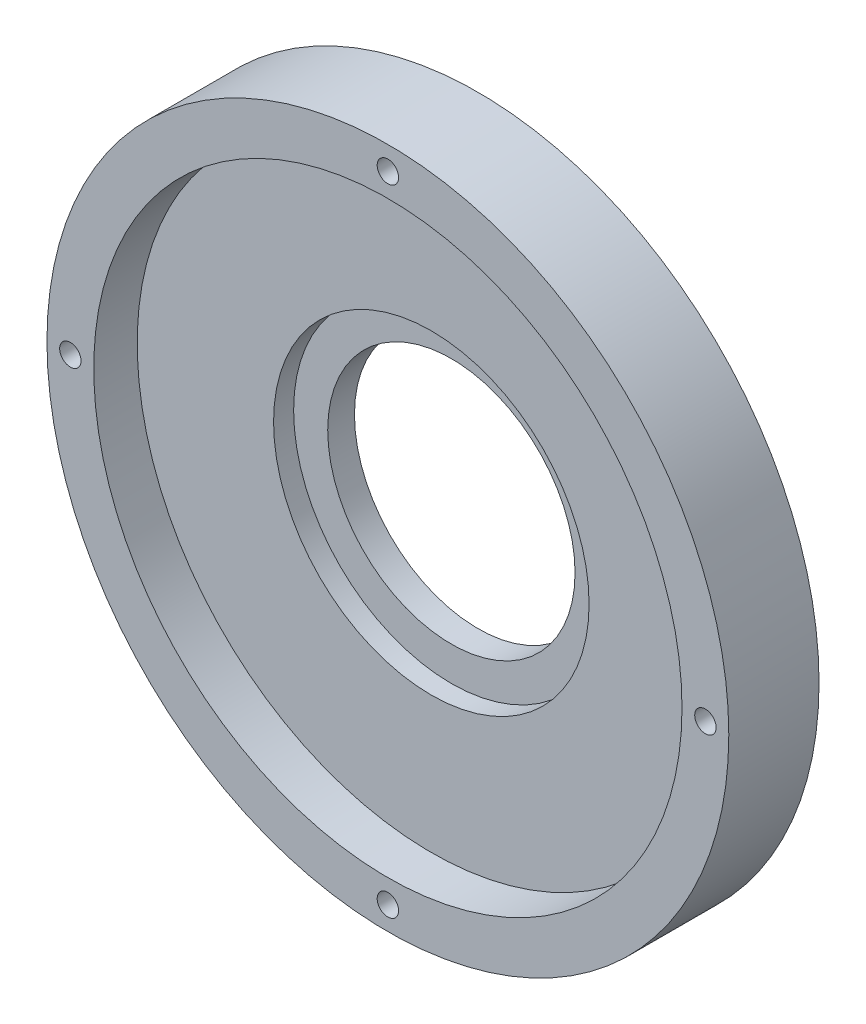
SolidWorks part; units mm, degrees
ref_plane "Front Plane" through (0, 0, 0) normal (0, 0, 1) x (1, 0, 0)
ref_plane "Top Plane" through (0, 0, 0) normal (0, 1, 0) x (1, 0, 0)
ref_plane "Right Plane" through (0, 0, 0) normal (1, 0, 0) x (0, 0, -1)
sketch "Sketch1" plane through (0, 0, 0) normal (0, 0, 1) x (1, 0, 0)
  circle A0 centre (0, 0) radius 51
  dimension "D1" = 102
extrude "Boss-Extrude1" add sketch "Sketch1" along normal blind 13.5
shell "Shell1" thickness 7
sketch "Sketch2" plane through (0, 0, 0) normal (0, 0, -1) x (-1, 0, 0)
  circle A0 centre (0, 0) radius 18.5
  dimension "D1" = 37
extrude "Cut-Extrude1" cut sketch "Sketch2" against normal up to surface (7 mm away) up to face at (44, 0, 7)
sketch "Sketch3" plane through (0, 0, 7) normal (0, 0, 1) x (1, 0, 0)
  circle A0 centre (0, 0) radius 23.6
  dimension "D1" = 47.2
extrude "Cut-Extrude2" cut sketch "Sketch3" against normal offset from surface (3 mm away) 4 up to face at (-18.5, 0, 0)
sketch "Sketch5" plane through (0, 0, 13.5) normal (0, 0, 1) x (1, 0, 0)
  circle A0 centre (0, 0) radius 47.5 construction
  circle A1 centre (0, 47.5) radius 1.6
  circle A2 centre (47.5, 0) radius 1.6
  circle A3 centre (0, -47.5) radius 1.6
  circle A4 centre (-47.5, 0) radius 1.6
  point P21 (0, 0)
  dimension "D1" = 95
  dimension "D2" = 3.2
  dimension "D3" = 4
extrude "Cut-Extrude3" cut sketch "Sketch5" against normal up to surface (13.5 mm away) up to face at (-18.5, 0, 0)
sketch "Sketch6" plane through (0, 0, 0) normal (0, 0, -1) x (-1, 0, 0)
  line L0 (0, 0) -> (-36.0624, 36.0624) construction
  line L1 (0, 0) -> (-51, 0) construction
  circle A0 centre (0, 0) radius 51 construction
  circle A1 centre (0, 0) radius 47.5 construction
  circle A2 centre (-33.5876, 33.5876) radius 2.25
  circle A3 centre (33.5876, 33.5876) radius 2.25
  circle A4 centre (33.5876, -33.5876) radius 2.25
  circle A5 centre (-33.5876, -33.5876) radius 2.25
  point P20 (0, 0)
  dimension "D2" = 4.5
  dimension "D1" = 45
  dimension "D3" = 4
extrude "Cut-Extrude4" cut sketch "Sketch6" against normal blind 6
sketch "Sketch7" plane through (0, 0, 7) normal (0, 0, 1) x (1, 0, 0)
